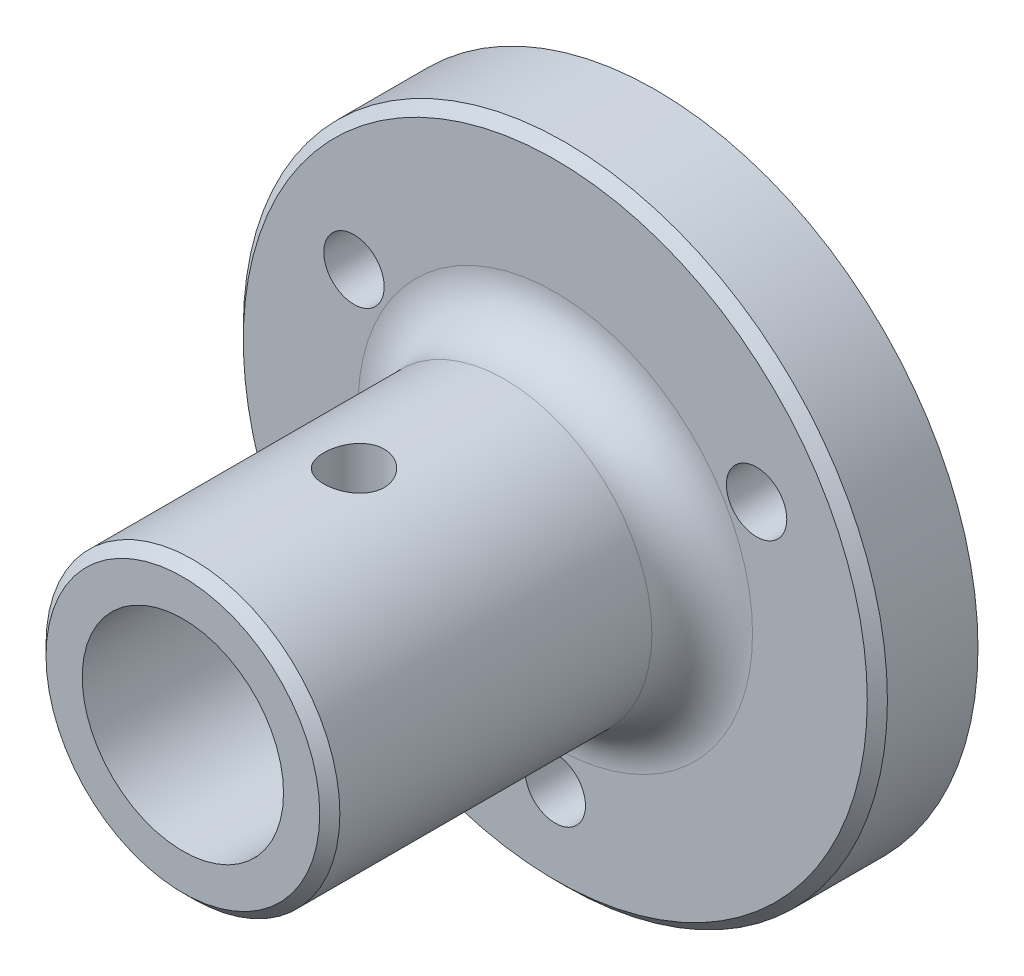
SolidWorks part; units mm, degrees
ref_plane "Front Plane" through (0, 0, 0) normal (0, 0, 1) x (1, 0, 0)
ref_plane "Top Plane" through (0, 0, 0) normal (0, 1, 0) x (1, 0, 0)
ref_plane "Right Plane" through (0, 0, 0) normal (1, 0, 0) x (0, 0, -1)
sketch "Sketch1" plane through (0, 0, 0) normal (0, 0, 1) x (1, 0, 0)
  line L0 (0, 0) -> (0, -23.094) construction
  line L1 (0, 0) -> (20, 11.547) construction
  line L2 (0, 0) -> (-20, 11.547) construction
  line L3 (20, 11.547) -> (0, -23.094) construction
  line L4 (0, -23.094) -> (-20, 11.547) construction
  line L5 (-20, 11.547) -> (20, 11.547) construction
  circle A0 centre (0, 0) radius 32
  circle A1 centre (20, 11.547) radius 3
  circle A2 centre (0, -23.094) radius 3
  circle A3 centre (-20, 11.547) radius 3
  circle A4 centre (0, 0) radius 10 construction
  dimension "D1" = 64
  dimension "D7" = 6
  dimension "D8" = 6
  dimension "D9" = 6
  dimension "D10" = 20
  dimension "D2" = 40
  dimension "D3" = 40
extrude "Boss-Extrude1" add sketch "Sketch1" along normal blind 10
sketch "Sketch2" plane through (0, 0, 10) normal (0, 0, 1) x (1, 0, 0)
  circle A0 centre (0, 0) radius 10
  circle A1 centre (0, 0) radius 14.6
  dimension "D1" = 20
  dimension "D2" = 4.6
extrude "Boss-Extrude2" add sketch "Sketch2" along normal blind 37
sketch "Sketch3" plane through (0, 0, 0) normal (0, 1, 0) x (1, 0, 0)
  line L0 (0, -10) -> (0, -30)
  line L1 (-14.6, -10) -> (14.6, -10) construction
  circle A0 centre (0, -30) radius 3
  dimension "D2" = 6
  dimension "D1" = 20
extrude "Cut-Extrude1" cut sketch "Sketch3" against normal through all both and the other way through all
fillet "圆角1" radius 5 1 edges at (14.6, 0, 10)
chamfer "倒角1" distance 1 angle 45 2 edges at (14.6, 0, 47) (32, 0, 10)
